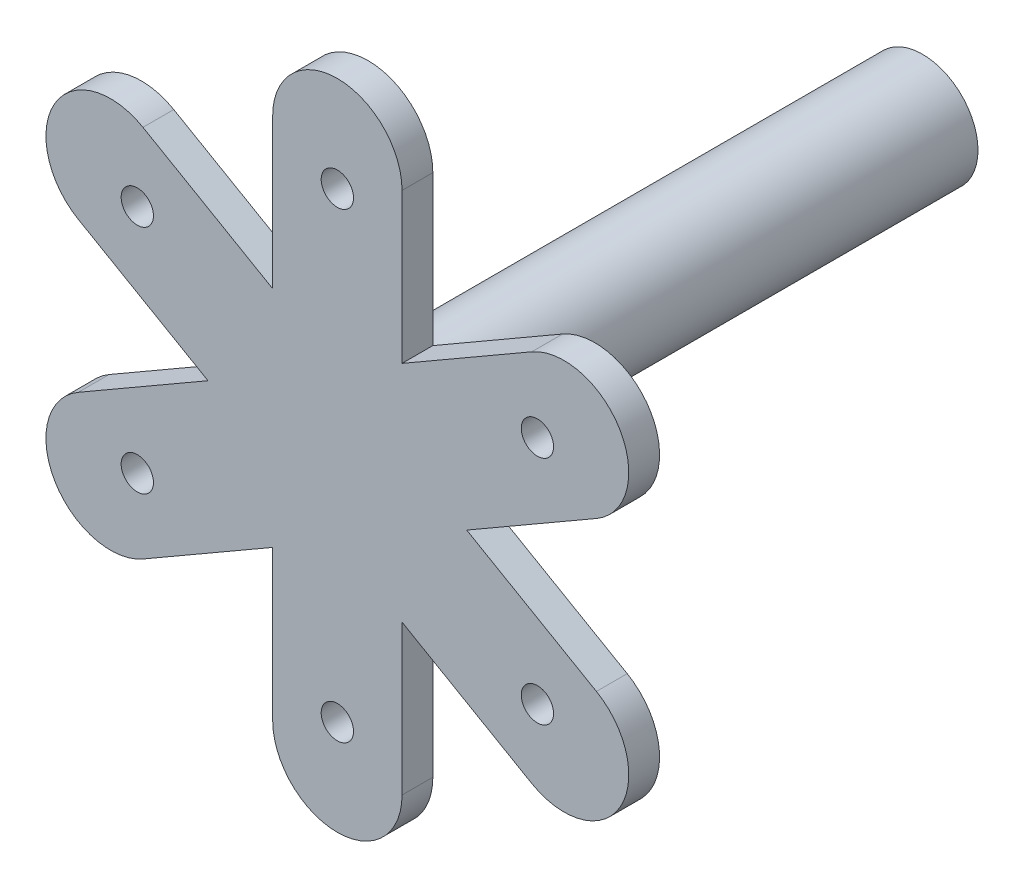
SolidWorks part; units mm, degrees
ref_plane "前视基准面" through (0, 0, 0) normal (0, 0, 1) x (1, 0, 0)
ref_plane "上视基准面" through (0, 0, 0) normal (0, 1, 0) x (1, 0, 0)
ref_plane "右视基准面" through (0, 0, 0) normal (1, 0, 0) x (0, 0, -1)
sketch "草图1" plane through (0, 0, 0) normal (0, 0, 1) x (1, 0, 0)
  line L0 (0, 0) -> (0, -85) construction
  line L1 (21, 0) -> (21, -48.6269)
  line L2 (-21, 0) -> (-21, -48.6269)
  line L3 (84.1122, -60.6865) -> (42, -85)
  line L4 (63.1122, -24.3135) -> (21, -48.6269)
  line L5 (63.1122, -145.6865) -> (21, -121.3731)
  line L6 (84.1122, -109.3135) -> (42, -85)
  line L7 (-21, -170) -> (-21, -121.3731)
  line L8 (21, -170) -> (21, -121.3731)
  line L9 (-84.1122, -109.3135) -> (-42, -85)
  line L10 (-63.1122, -145.6865) -> (-21, -121.3731)
  line L11 (-63.1122, -24.3135) -> (-21, -48.6269)
  line L12 (-84.1122, -60.6865) -> (-42, -85)
  arc A0 (21, 0) -> (-21, 0) centre (0, 0) ccw
  arc A3 (84.1122, -60.6865) -> (63.1122, -24.3135) centre (73.6122, -42.5) ccw
  arc A5 (63.1122, -145.6865) -> (84.1122, -109.3135) centre (73.6122, -127.5) ccw
  arc A7 (-21, -170) -> (21, -170) centre (0, -170) ccw
  arc A9 (-84.1122, -109.3135) -> (-63.1122, -145.6865) centre (-73.6122, -127.5) ccw
  arc A11 (-63.1122, -24.3135) -> (-84.1122, -60.6865) centre (-73.6122, -42.5) ccw
  circle A26 centre (0, -10) radius 5.25
  circle A27 centre (64.9519, -47.5) radius 5.25
  circle A28 centre (64.9519, -122.5) radius 5.25
  circle A29 centre (0, -160) radius 5.25
  circle A30 centre (-64.9519, -122.5) radius 5.25
  circle A31 centre (-64.9519, -47.5) radius 5.25
  point P3 (0, -42.5)
  point P37 (0, -85)
  point P43 (0, -85)
  dimension "D2" = 10.5
  dimension "D5" = 75
  dimension "D1" = 42
  dimension "D3" = 85
  dimension "D4" = 6
  dimension "D6" = 6
extrude "凸台-拉伸1" add sketch "草图1" along normal blind 10
sketch "草图2" plane through (0, 0, 0) normal (0, 0, -1) x (-1, 0, 0)
  circle A0 centre (0, -85.2035) radius 18
  dimension "D1" = 36
extrude "凸台-拉伸2" add sketch "草图2" along normal blind 180
